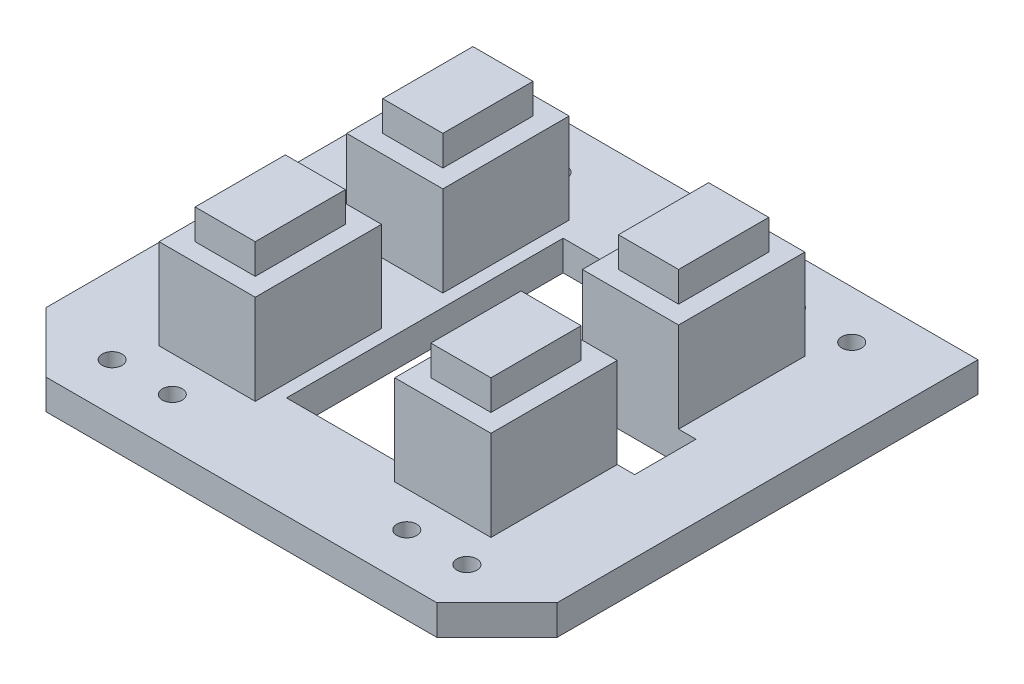
SolidWorks part; units mm, degrees
material "PLA+ esun"
ref_plane "Front Plane" through (0, 0, 0) normal (0, 0, 1) x (1, 0, 0)
ref_plane "Top Plane" through (0, 0, 0) normal (0, 1, 0) x (1, 0, 0)
ref_plane "Right Plane" through (0, 0, 0) normal (1, 0, 0) x (0, 0, -1)
sketch "Sketch1" plane through (0, 0, 0) normal (0, 1, 0) x (1, 0, 0)
  line L0 (0, 0) -> (49.8029, 0) construction
  line L1 (-77.5, 77.5) -> (77.5, 77.5)
  line L2 (-77.5, 77.5) -> (-77.5, -77.5)
  line L3 (-77.5, -77.5) -> (77.5, -77.5)
  line L4 (77.5, 77.5) -> (77.5, -77.5)
  line L5 (-77.5, 77.5) -> (77.5, -77.5) construction
  line L6 (-77.5, -77.5) -> (77.5, 77.5) construction
  line L7 (-9.5, 23) -> (9.5, 23)
  line L8 (-9.5, 23) -> (-9.5, -23)
  line L9 (-9.5, -23) -> (9.5, -23)
  line L10 (9.5, 23) -> (9.5, -23)
  line L11 (-9.5, 23) -> (9.5, -23) construction
  line L12 (-9.5, -23) -> (9.5, 23) construction
  line L14 (0, 0) -> (0, 35.7746) construction
  line L17 (-77.5, -77.5) -> (-42.5, -77.5)
  line L18 (-77.5, -77.5) -> (-77.5, -24.25)
  line L19 (-77.5, -24.25) -> (-42.5, -24.25)
  line L20 (-42.5, -77.5) -> (-42.5, -24.25)
  line L21 (-77.5, 24.25) -> (-42.5, 24.25)
  line L22 (-42.5, 77.5) -> (-42.5, 24.25)
  line L23 (42.5, -77.5) -> (42.5, -24.25)
  line L24 (77.5, -24.25) -> (42.5, -24.25)
  line L25 (42.5, 77.5) -> (42.5, 24.25)
  line L26 (77.5, 24.25) -> (42.5, 24.25)
  line L27 (20, -40) -> (42.5, -40)
  line L28 (-42.5, 24.25) -> (-77.5, 24.25)
  line L29 (-42.5, 24.25) -> (-42.5, -24.25)
  line L30 (-42.5, -24.25) -> (-77.5, -24.25)
  line L31 (-77.5, 24.25) -> (-77.5, -24.25)
  line L32 (42.5, 24.25) -> (77.5, 24.25)
  line L33 (42.5, 24.25) -> (42.5, -24.25)
  line L34 (42.5, -24.25) -> (77.5, -24.25)
  line L35 (77.5, 24.25) -> (77.5, -24.25)
  line L36 (-42.5, 77.5) -> (42.5, 77.5)
  line L37 (-42.5, 77.5) -> (-42.5, 40)
  line L38 (-42.5, 40) -> (42.5, 40)
  line L39 (42.5, 77.5) -> (42.5, 40)
  line L40 (-42.5, -77.5) -> (42.5, -77.5)
  line L41 (-42.5, -77.5) -> (-42.5, -40)
  line L42 (-42.5, -40) -> (-20, -40)
  line L43 (42.5, -77.5) -> (42.5, -40)
  line L45 (-20, -40) -> (-20, -77.5)
  line L46 (-20, -77.5) -> (20, -77.5)
  line L47 (20, -40) -> (20, -77.5)
  line L49 (-20, -77.5) -> (20, -77.5)
  line L50 (-20, -77.5) -> (-20, -40)
  line L51 (-20, -40) -> (20, -40)
  line L52 (20, -77.5) -> (20, -40)
  circle A1 centre (29.5, 32) radius 1.65
  circle A2 centre (19.5, 32) radius 1.65
  circle A3 centre (19.5, -32) radius 1.65
  circle A4 centre (29.5, -32) radius 1.65
  circle A5 centre (-29.5, -32) radius 1.65
  circle A6 centre (-19.5, -32) radius 1.65
  circle A7 centre (-19.5, 32) radius 1.65
  circle A8 centre (-29.5, 32) radius 1.65
  point P0 (0, 0)
  point P6 (0, 0)
  point P13 (0, 0)
  dimension "D5" = 9
  dimension "D8" = 20
  dimension "D9" = 53.25
  dimension "D6" = 3.3
  dimension "D1" = 155
  dimension "D2" = 155
  dimension "D3" = 46
  dimension "D4" = 19
  dimension "D7" = 2
  dimension "D10" = 35
  dimension "D11" = 37.5
  dimension "D12" = 37.5
  dimension "D13" = 22.5
  dimension "D14" = 22.5
extrude "Boss-Extrude3" add sketch "Sketch1" along normal blind 5 contours L4 L26 L25 L1 L22 L21 L2 L19 L20 L3 L23 L24 A7 A6 A5 A3 A2 A1 L7 L10 L9 L8 A4 A8
chamfer "Chamfer1" distance 10 angle 45 2 edges at (42.5, 2.5, 40) (-42.5, 2.5, 40)
sketch "Sketch6" plane through (0, 5, 0) normal (0, 1, 0) x (1, 0, 0)
  line L0 (-24.6, 8.1) -> (-14.6, 8.1)
  line L9 (-14.6, 8.1) -> (-14.6, 23.1)
  line L10 (-24.6, 8.1) -> (-24.6, 23.1)
  line L11 (-24.7, 8) -> (-14.5, 8)
  line L12 (-24.7, 23.2) -> (-14.5, 23.2)
  line L13 (-24.7, 23.2) -> (-24.7, -23.2)
  line L14 (-24.7, -23.2) -> (-14.5, -23.2)
  line L15 (-14.5, 23.2) -> (-14.5, -23.2)
  line L16 (9.5, 23) -> (-9.5, 23)
  line L17 (9.5, 23) -> (9.5, -23)
  line L18 (9.5, -23) -> (-9.5, -23)
  line L19 (-9.5, 23) -> (-9.5, -23)
  line L20 (9.5, 23) -> (-9.5, -23) construction
  line L21 (9.5, -23) -> (-9.5, 23) construction
  line L22 (-24.7, -8) -> (-14.5, -8)
  line L23 (0, 0) -> (0, -14.0514) construction
  line L24 (24.6, 23.1) -> (14.6, 23.1)
  line L29 (14.6, -8.1) -> (14.6, -23.1)
  line L30 (0, 0) -> (7.1407, 0) construction
  line L35 (-24.6, -8.1) -> (-14.6, -8.1)
  line L36 (-24.6, -8.1) -> (-24.6, -23.1)
  line L37 (-24.6, -23.1) -> (-14.6, -23.1)
  line L38 (-14.6, -8.1) -> (-14.6, -23.1)
  line L39 (-24.6, 23.1) -> (-14.6, 23.1)
  line L40 (24.6, -23.1) -> (14.6, -23.1)
  line L41 (24.6, -8.1) -> (24.6, -23.1)
  line L42 (24.6, -8.1) -> (14.6, -8.1)
  line L43 (24.7, -8) -> (14.5, -8)
  line L44 (14.5, 23.2) -> (14.5, -23.2)
  line L45 (24.7, -23.2) -> (14.5, -23.2)
  line L46 (24.7, 23.2) -> (24.7, -23.2)
  line L47 (24.7, 23.2) -> (14.5, 23.2)
  line L48 (24.7, 8) -> (14.5, 8)
  line L49 (24.6, 8.1) -> (24.6, 23.1)
  line L50 (14.6, 8.1) -> (14.6, 23.1)
  line L51 (24.6, 8.1) -> (14.6, 8.1)
  point P4 (0, 0)
  dimension "D1" = 0.2
  dimension "D2" = 5
  dimension "D3" = 0.2
  dimension "D4" = 10.2
  dimension "D5" = 15.2
  dimension "D6" = 15.2
  dimension "D7" = 0.1
  dimension "D8" = 0.1
  dimension "D9" = 0.1
  dimension "D10" = 0.1
extrude "Boss-Extrude4" add sketch "Sketch6" along normal blind 20 contours L51 L49 L24 L50 | L39 L10 L0 L9 | L38 L35 L36 L37 | L41 L42 L29 L40
sketch "Sketch8" plane through (0, 5, 0) normal (0, 1, 0) x (1, 0, 0)
  line L0 (0, 0) -> (0, -16.476) construction
  line L1 (-27.6, 26.1) -> (-11.6, 26.1)
  line L2 (-27.6, 26.1) -> (-27.6, -26.1)
  line L3 (-27.6, -26.1) -> (-11.6, -26.1)
  line L4 (-11.6, 26.1) -> (-11.6, -26.1)
  line L5 (-24.6, 23.1) -> (-14.6, 23.1) construction
  line L6 (-24.6, 8.1) -> (-24.6, 23.1) construction
  line L7 (-14.6, 8.1) -> (-14.6, 23.1) construction
  line L8 (-24.6, -23.1) -> (-14.6, -23.1) construction
  line L9 (11.6, 26.1) -> (11.6, -26.1)
  line L10 (27.6, -26.1) -> (11.6, -26.1)
  line L11 (27.6, 26.1) -> (27.6, -26.1)
  line L12 (27.6, 26.1) -> (11.6, 26.1)
  line L13 (-24.6, 8.1) -> (-14.6, 8.1) construction
  line L14 (-27.6, 5.1) -> (-11.6, 5.1)
  line L15 (-27.6, 5.1) -> (-27.6, -5.1)
  line L16 (-27.6, -5.1) -> (-11.6, -5.1)
  line L17 (-11.6, 5.1) -> (-11.6, -5.1)
  line L18 (-24.6, -8.1) -> (-14.6, -8.1) construction
  line L19 (27.6, -5.1) -> (11.6, -5.1)
  line L20 (27.6, 5.1) -> (11.6, 5.1)
  line M8 (24.6, -8.1) -> (24.6, -23.1)
  line M9 (24.6, -23.1) -> (14.6, -23.1)
  line M10 (14.6, -23.1) -> (14.6, -8.1)
  line M11 (14.6, -8.1) -> (24.6, -8.1)
  line M12 (-14.6, -8.1) -> (-14.6, -23.1)
  line M13 (-14.6, -23.1) -> (-24.6, -23.1)
  line M14 (-24.6, -23.1) -> (-24.6, -8.1)
  line M15 (-24.6, -8.1) -> (-14.6, -8.1)
  line M16 (-24.6, 23.1) -> (-14.6, 23.1)
  line M17 (-14.6, 23.1) -> (-14.6, 8.1)
  line M18 (-14.6, 8.1) -> (-24.6, 8.1)
  line M19 (-24.6, 8.1) -> (-24.6, 23.1)
  line M20 (24.6, 8.1) -> (14.6, 8.1)
  line M21 (14.6, 8.1) -> (14.6, 23.1)
  line M22 (14.6, 23.1) -> (24.6, 23.1)
  line M23 (24.6, 23.1) -> (24.6, 8.1)
  dimension "D1" = 3
  dimension "D2" = 3
  dimension "D3" = 3
  dimension "D4" = 3
  dimension "D5" = 3
  dimension "D6" = 3
extrude "Boss-Extrude5" add sketch "Sketch8" along normal blind 15 contours L2 L14 L4 L1 M19 M16 M17 M18 | L16 L2 L3 L4 M15 M12 M13 M14 | L11 L19 L9 L10 M11 M8 M9 M10 | L20 L11 L12 L9 M23 M20 M21 M22
sketch "Sketch5" plane through (0, 0, 0) normal (0, -1, 0) x (1, 0, 0)
  line L0 (9.5, -23) -> (9.5, 23) construction
  line L1 (14.5, 5.1) -> (30.5, 5.1)
  line L2 (14.5, 5.1) -> (14.5, -5.1)
  line L3 (14.5, -5.1) -> (30.5, -5.1)
  line L4 (30.5, 5.1) -> (30.5, -5.1)
  line L5 (-9.5, -23) -> (9.5, -23) construction
  line L6 (-9.5, 23) -> (9.5, 23) construction
  dimension "D1" = 5
  dimension "D2" = 16
  dimension "D3" = 17.9
  dimension "D4" = 17.9
extrude "Cut-Extrude1" cut sketch "Sketch5" against normal through all
